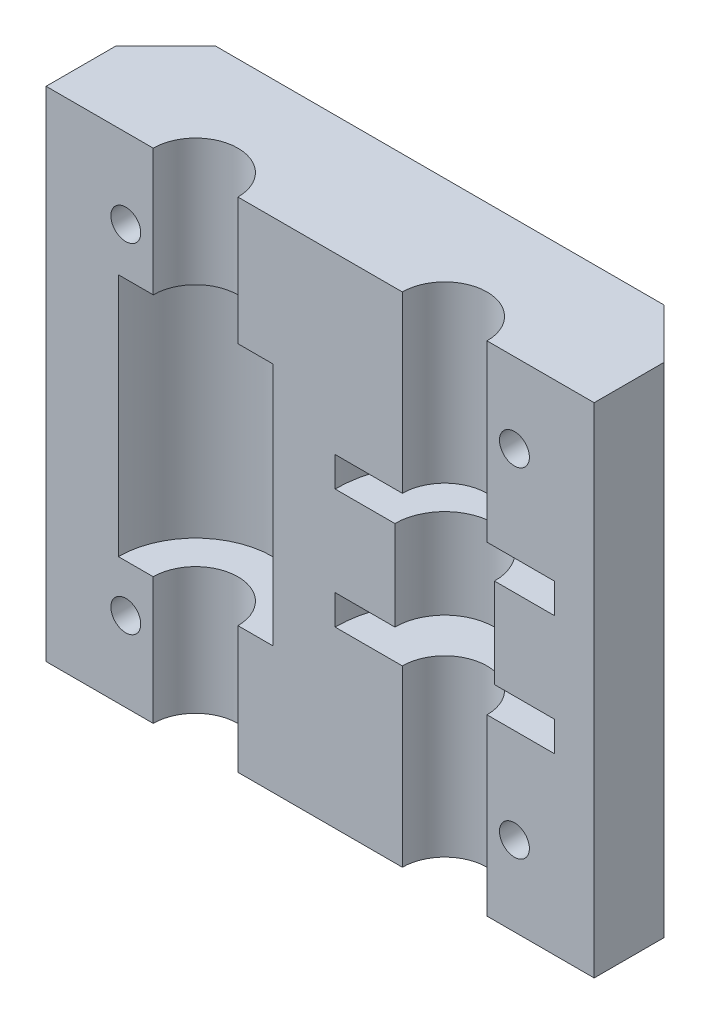
SolidWorks part; units mm, degrees
ref_plane "Plan de face" through (0, 0, 0) normal (0, 0, 1) x (1, 0, 0)
ref_plane "Plan de dessus" through (0, 0, 0) normal (0, 1, 0) x (1, 0, 0)
ref_plane "Plan de droite" through (0, 0, 0) normal (1, 0, 0) x (0, 0, -1)
sketch "Esquisse1" plane through (0, 0, 0) normal (0, 0, 1) x (1, 0, 0)
  line L1 (-27.5, -25) -> (27.5, -25)
  line L2 (-27.5, -25) -> (-27.5, 25)
  line L3 (-27.5, 25) -> (27.5, 25)
  line L4 (27.5, -25) -> (27.5, 25)
  line L5 (-27.5, -25) -> (27.5, 25) construction
  line L6 (-27.5, 25) -> (27.5, -25) construction
  point P0 (0, 0)
  dimension "D1" = 55
  dimension "D2" = 50
extrude "Boss.-Extru.1" add sketch "Esquisse1" along normal blind 12
sketch "Esquisse2" plane through (0, 25, 0) normal (0, 1, 0) x (1, 0, 0)
  line L0 (27.5, -12) -> (-27.5, -12) construction
  line L1 (-27.5, -12) -> (-27.5, 0) construction
  line L2 (27.5, -12) -> (27.5, 0) construction
  circle A0 centre (-12.5, -12) radius 4.25
  circle A1 centre (12.5, -12) radius 4.25
  dimension "D1" = 8.5
  dimension "D3" = 8.5
  dimension "D2" = 15
  dimension "D4" = 15
extrude "Enlèv. mat.-Extru.1" cut sketch "Esquisse2" against normal through all
ref_plane "Plan2" through (0, 7.5, 0) normal (0, 1, 0) x (1, 0, 0)
sketch "Esquisse3" plane through (0, 0, 0) normal (0, 1, 0) x (1, 0, 0)
  circle A0 centre (-12.5, -12) radius 7.75
  dimension "D1" = 15.5
extrude "Enlèv. mat.-Extru.2" cut sketch "Esquisse3" against normal blind 12.25 and the other way blind 12.25
sketch "Esquisse4" plane through (0, 7.5, 0) normal (0, 1, 0) x (1, 0, 0)
  circle A0 centre (12.5, -12) radius 11
  dimension "D1" = 22
extrude "Enlèv. mat.-Extru.3" cut sketch "Esquisse4" against normal blind 3
sketch "Esquisse5" plane through (0, 7.5, 0) normal (0, 1, 0) x (1, 0, 0)
  circle A0 centre (12.5, -12) radius 5
  dimension "D1" = 10
extrude "Enlèv. mat.-Extru.4" cut sketch "Esquisse5" against normal blind 15
chamfer "Chanfrein1" [suppressed] distance 10 angle 45
sketch "Esquisse6" plane through (0, 0, 0) normal (0, 0, -1) x (-1, 0, 0)
  line L0 (0, -25) -> (0, 25) construction
  line L1 (27.5, -25) -> (-27.5, -25) construction
  line L2 (-27.5, 25) -> (27.5, 25) construction
  line L3 (27.5, 25) -> (27.5, -25) construction
  line L4 (27.5, 0) -> (-27.5, 0) construction
  line L5 (-27.5, -25) -> (-27.5, 25) construction
  circle A0 centre (19.5, -17) radius 1.5
  circle A1 centre (-19.5, -17) radius 1.5
  circle A2 centre (-19.5, 17) radius 1.5
  circle A3 centre (19.5, 17) radius 1.5
  dimension "D1" = 3
  dimension "D2" = 8
  dimension "D3" = 8
extrude "Enlèv. mat.-Extru.5" cut sketch "Esquisse6" against normal through all both and the other way through all
sketch "Esquisse7" plane through (0, 0, 0) normal (0, 0, -1) x (-1, 0, 0)
  line L0 (0, -25) -> (0, 25) construction
  line L1 (27.5, -25) -> (-27.5, -25) construction
  line L2 (-27.5, 25) -> (27.5, 25) construction
  line L3 (27.5, 0) -> (-27.5, 0) construction
  line L4 (27.5, 25) -> (27.5, -25) construction
  line L5 (-27.5, -25) -> (-27.5, 25) construction
  circle A0 centre (19.5, -17) radius 2.5
  circle A1 centre (19.5, 17) radius 2.5
  circle A2 centre (-19.5, 17) radius 2.5
  circle A3 centre (-19.5, -17) radius 2.5
  dimension "D1" = 5
extrude "Enlèv. mat.-Extru.6" cut sketch "Esquisse7" against normal blind 4
chamfer "Chanfrein3" distance 5 angle 45 2 edges at (27.5, 0, 0) (-27.5, 0, 0)
mirror "Symétrie2" about plane through (0, 0, 0) normal (0, 1, 0) of "Enlèv. mat.-Extru.3"
sketch "Esquisse8" plane through (0, 0, 0) normal (0, 0, -1) x (-1, 0, 0)
  line L0 (22.5, -25) -> (-22.5, -25) construction
  line L1 (-8.5398, -48.108) -> (8.5398, -48.108)
  line L2 (-8.5398, -48.108) -> (-8.5398, -1.892)
  line L3 (-8.5398, -1.892) -> (8.5398, -1.892)
  line L4 (8.5398, -48.108) -> (8.5398, -1.892)
  line L5 (-8.5398, -48.108) -> (8.5398, -1.892) construction
  line L6 (-8.5398, -1.892) -> (8.5398, -48.108) construction
  point P0 (0, -25)
